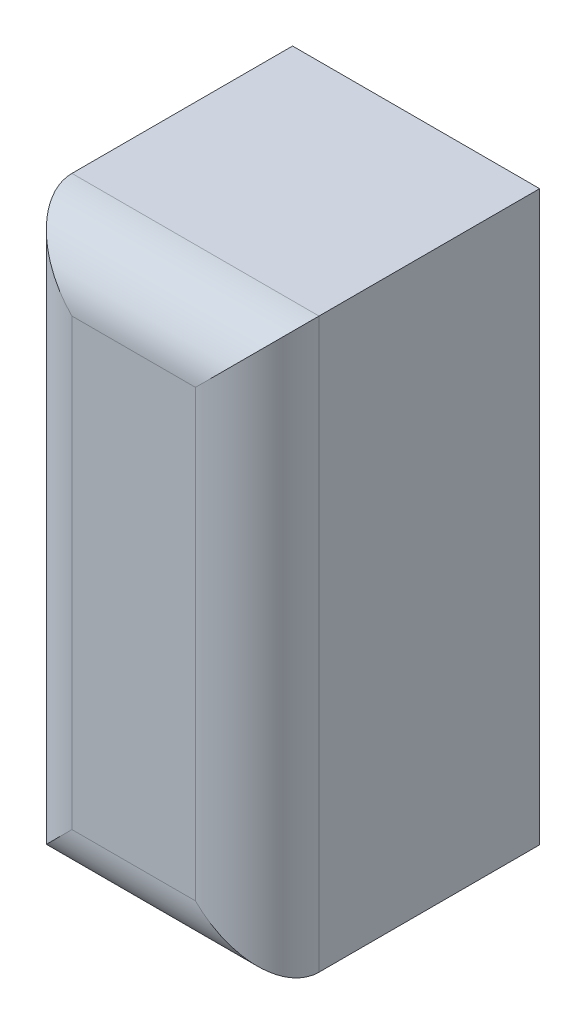
SolidWorks part; units mm, degrees
ref_plane "Front Plane" through (0, 0, 0) normal (0, 0, 1) x (1, 0, 0)
ref_plane "Top Plane" through (0, 0, 0) normal (0, 1, 0) x (1, 0, 0)
ref_plane "Right Plane" through (0, 0, 0) normal (1, 0, 0) x (0, 0, -1)
sketch "Sketch1" plane through (0, 0, 0) normal (0, 0, 1) x (1, 0, 0)
  line L1 (-10, 23) -> (10, 23)
  line L2 (-10, 23) -> (-10, -23)
  line L3 (-10, -23) -> (10, -23)
  line L4 (10, 23) -> (10, -23)
  line L5 (-10, 23) -> (10, -23) construction
  line L6 (-10, -23) -> (10, 23) construction
  point P0 (0, 0)
  dimension "D1" = 46
  dimension "D2" = 20
extrude "Boss-Extrude1" add sketch "Sketch1" along normal blind 22.86
sketch "Sketch2" plane through (0, 0, 0) normal (0, 0, -1) x (-1, 0, 0)
  line L0 (0, 12.5) -> (0, -12.5) construction
  line L2 (10, -23) -> (-10, -23) construction
  line L3 (-10, -23) -> (-10, 23) construction
  circle A0 centre (0, 12.5) radius 6.05
  circle A1 centre (0, -12.5) radius 6.05
  point P6 (0, 0)
  dimension "D1" = 12.1
  dimension "D2" = 25
  dimension "D3" = 23
  dimension "D4" = 10
extrude "Cut-Extrude1" cut sketch "Sketch2" against normal blind 17.78
fillet "Fillet1" radius 5 4 edges at (0, -23, 22.86) (-10, 0, 22.86) (0, 23, 22.86) (10, 0, 22.86)
